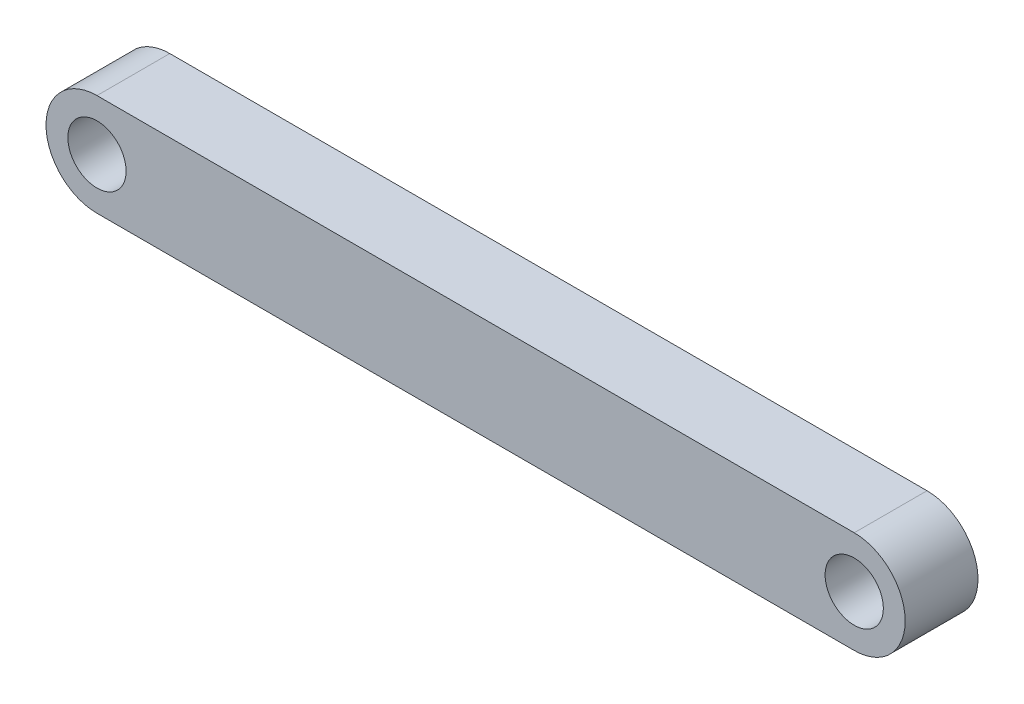
SolidWorks part; units mm, degrees
ref_plane "Plan de face" through (0, 0, 0) normal (0, 0, 1) x (1, 0, 0)
ref_plane "Plan de dessus" through (0, 0, 0) normal (0, 1, 0) x (1, 0, 0)
ref_plane "Plan de droite" through (0, 0, 0) normal (1, 0, 0) x (0, 0, -1)
sketch "Sketch1" plane through (0, 0, 0) normal (0, 0, 1) x (1, 0, 0)
  line L1 (-26, -3.5) -> (26, -3.5)
  line L2 (-26, -3.5) -> (-26, 3.5)
  line L3 (-26, 3.5) -> (26, 3.5)
  line L4 (26, -3.5) -> (26, 3.5)
  line L5 (-26, -3.5) -> (26, 3.5) construction
  line L6 (-26, 3.5) -> (26, -3.5) construction
  circle A0 centre (-26, 0) radius 3.5
  circle A1 centre (26, 0) radius 3.5
  circle A2 centre (-26, 0) radius 2
  circle A3 centre (26, 0) radius 2
  point P0 (0, 0)
  dimension "D3" = 4
  dimension "D4" = 4
  dimension "D1" = 52
  dimension "D2" = 7
extrude "Boss-Extrude1" add sketch "Sketch1" along normal blind 5 contours A1 L3 A0 L1 | A3 L4 A1 | A3 L4 A1 | A2
